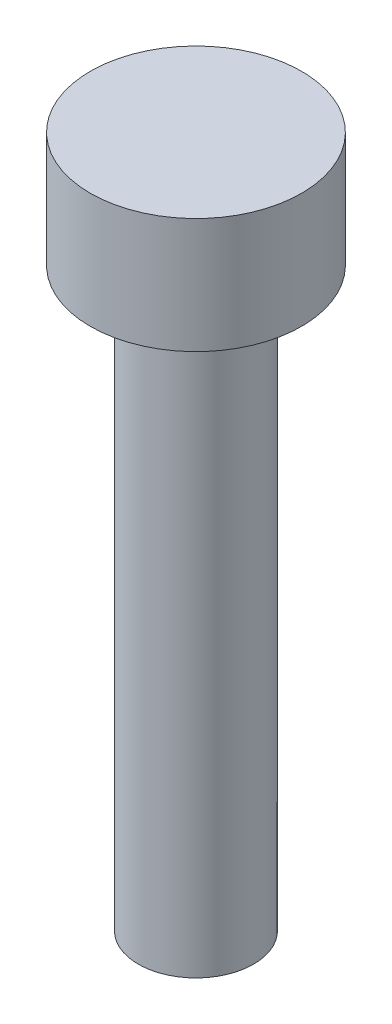
SolidWorks part; units mm, degrees
ref_plane "Front Plane" through (0, 0, 0) normal (0, 0, 1) x (1, 0, 0)
ref_plane "Top Plane" through (0, 0, 0) normal (0, 1, 0) x (1, 0, 0)
ref_plane "Right Plane" through (0, 0, 0) normal (1, 0, 0) x (0, 0, -1)
sketch "Sketch1" plane through (0, 0, 0) normal (0, 1, 0) x (1, 0, 0)
  circle A0 centre (0, 0) radius 2.75
  dimension "D1" = 5.5
extrude "Boss-Extrude1" add sketch "Sketch1" along normal blind 3
sketch "Sketch2" plane through (0, 0, 0) normal (0, -1, 0) x (1, 0, 0)
  circle A0 centre (0, 0) radius 1.5
extrude "Boss-Extrude2" add sketch "Sketch2" along normal blind 15
